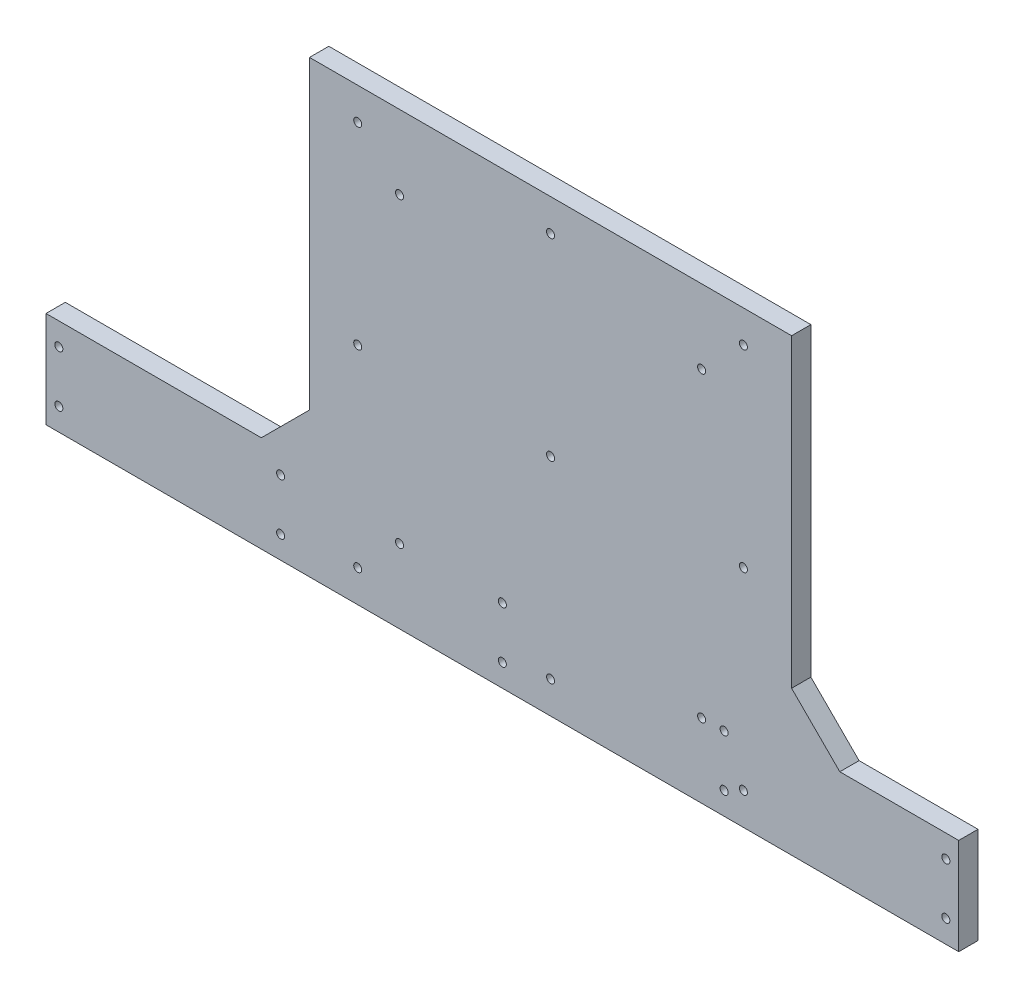
SolidWorks part; units mm, degrees
ref_plane "Plan de face" through (0, 0, 0) normal (0, 0, 1) x (1, 0, 0)
ref_plane "Plan de dessus" through (0, 0, 0) normal (0, 1, 0) x (1, 0, 0)
ref_plane "Plan de droite" through (0, 0, 0) normal (1, 0, 0) x (0, 0, -1)
sketch "Esquisse1" plane through (0, 0, 0) normal (0, 0, 1) x (1, 0, 0)
  line L1 (0, 0) -> (150, 0)
  line L2 (0, 0) -> (0, 140)
  line L3 (0, 140) -> (150, 140)
  line L4 (150, 0) -> (150, 140)
  dimension "D1" = 150
  dimension "D2" = 140
extrude "Boss.-Extru.1" add sketch "Esquisse1" along normal blind 6
sketch "Esquisse2" plane through (0, 0, 6) normal (0, 0, 1) x (1, 0, 0)
  line L0 (75, 0) -> (75, 140) construction
  line L1 (0, 0) -> (150, 0) construction
  line L2 (150, 140) -> (0, 140) construction
  line L3 (75, 70) -> (0, 70) construction
  line L4 (0, 140) -> (0, 0) construction
  circle A0 centre (28, 117) radius 1.25
  circle A1 centre (122, 117) radius 1.25
  circle A2 centre (122, 23) radius 1.25
  circle A3 centre (28, 23) radius 1.25
  dimension "D1" = 94
  dimension "D2" = 94
  dimension "D3" = 2.5
extrude "Enlèv. mat.-Extru.1" cut sketch "Esquisse2" against normal through all
sketch "Esquisse3" plane through (0, 0, 6) normal (0, 0, 1) x (1, 0, 0)
  line L0 (0, 10) -> (150, 10) construction
  line L1 (0, 140) -> (0, 0) construction
  line L2 (150, 0) -> (150, 140) construction
  line L3 (75, 10) -> (75, 140) construction
  line L4 (150, 140) -> (0, 140) construction
  line L5 (0, 70) -> (150, 70) construction
  line L6 (0, 70) -> (150, 10) construction
  line L7 (150, 10) -> (75, 40) construction
  line L8 (75, 40) -> (150, 40) construction
  line L9 (0, 70) -> (150, 70) construction
  circle A0 centre (75, 10) radius 1.25
  circle A1 centre (15, 10) radius 1.25
  circle A2 centre (135, 10) radius 1.25
  circle A3 centre (135, 70) radius 1.25
  circle A4 centre (15, 70) radius 1.25
  circle A5 centre (75, 70) radius 1.25
  circle A6 centre (135, 130) radius 1.25
  circle A7 centre (15, 130) radius 1.25
  circle A8 centre (75, 130) radius 1.25
  dimension "D1" = 2.5
  dimension "D2" = 60
  dimension "D3" = 60
extrude "Enlèv. mat.-Extru.2" cut sketch "Esquisse3" against normal through all
sketch "Esquisse4" plane through (0, 0, 6) normal (0, 0, 1) x (1, 0, 0)
  line L0 (0, 140) -> (0, 0) construction
  line L1 (0, 0) -> (-82, 0)
  line L2 (0, 0) -> (0, 30)
  line L3 (0, 30) -> (-82, 30)
  line L4 (-82, 0) -> (-82, 30)
  line L6 (150, 0) -> (150, 140) construction
  line L7 (150, 0) -> (202, 0)
  line L8 (150, 0) -> (150, 30)
  line L9 (150, 30) -> (202, 30)
  line L10 (202, 0) -> (202, 30)
  point P6 (150, 74.1542)
  point P14 (0, 54.9811)
  point P15 (0, 0)
  dimension "D1" = 82
  dimension "D2" = 30
  dimension "D3" = 52
extrude "Boss.-Extru.2" add sketch "Esquisse4" against normal up to vertex (6 mm away)
sketch "Esquisse5" plane through (0, 0, 6) normal (0, 0, 1) x (1, 0, 0)
  line L0 (-78, 0) -> (-78, 30) construction
  line L1 (-82, 0) -> (202, 0) construction
  line L2 (0, 30) -> (-82, 30) construction
  line L3 (60, 0) -> (60, 30) construction
  line L4 (-78, 15) -> (-82, 15) construction
  line L5 (-82, 30) -> (-82, 0) construction
  line L6 (198, 15) -> (202, 15) construction
  line L7 (198, 0) -> (198, 30) construction
  line L8 (60, 15) -> (-78, 15) construction
  line L9 (-9, 15) -> (-9, 30) construction
  line L10 (60, 15) -> (64, 15) construction
  line L11 (60, 0) -> (60, 30) construction
  line L12 (-9, 15) -> (60, 0) construction
  line L13 (25.5, 7.5) -> (25.5, 15) construction
  line L14 (-9, 0) -> (-9, 30) construction
  line L15 (-9, 15) -> (-13, 15) construction
  line L16 (-9, 0) -> (-9, 30) construction
  line L17 (129, 0) -> (129, 30) construction
  line L18 (129, 15) -> (133, 15) construction
  line L19 (129, 0) -> (129, 30) construction
  line L20 (129, 15) -> (129, 30) construction
  circle A0 centre (-78, 23) radius 1.25
  circle A1 centre (-78, 7) radius 1.25
  circle A2 centre (198, 7) radius 1.25
  circle A3 centre (198, 23) radius 1.25
  circle A4 centre (60, 7) radius 1.25
  circle A5 centre (60, 23) radius 1.25
  circle A6 centre (-9, 23) radius 1.25
  circle A7 centre (-9, 7) radius 1.25
  circle A8 centre (129, 7) radius 1.25
  circle A9 centre (129, 23) radius 1.25
  point P15 (-80, 15)
  dimension "D2" = 2.5
  dimension "D3" = 8
  dimension "D1" = 4
extrude "Enlèv. mat.-Extru.3" cut sketch "Esquisse5" against normal through all
chamfer "Chanfrein1" distance 15 angle 45 2 edges at (0, 30, 3) (150, 30, 3)
